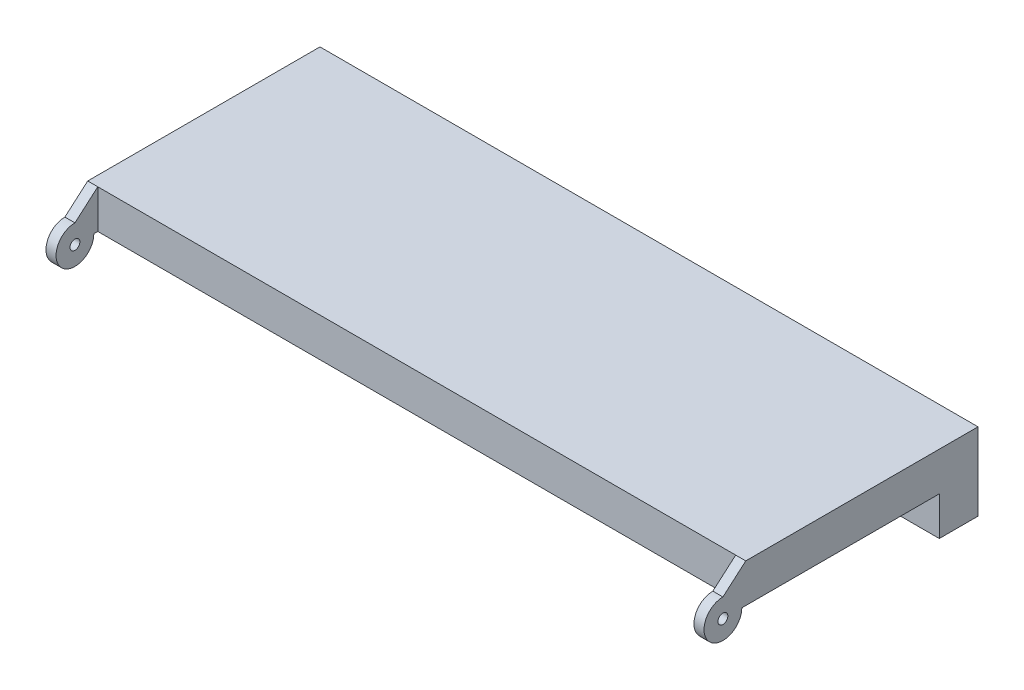
SolidWorks part; units mm, degrees
ref_plane "Front Plane" through (0, 0, 0) normal (0, 0, 1) x (1, 0, 0)
ref_plane "Top Plane" through (0, 0, 0) normal (0, 1, 0) x (1, 0, 0)
ref_plane "Right Plane" through (0, 0, 0) normal (1, 0, 0) x (0, 0, -1)
sketch "Sketch1" plane through (0, 0, 0) normal (0, 1, 0) x (1, 0, 0)
  line L1 (0, 0) -> (85, 0)
  line L2 (0, 0) -> (0, 30)
  line L3 (0, 30) -> (85, 30)
  line L4 (85, 0) -> (85, 30)
  dimension "D1" = 85
  dimension "D2" = 30
extrude "Top surface" add sketch "Sketch1" along normal blind 10
sketch "Sketch6" plane through (0, 0, 0) normal (-1, 0, 0) x (0, 0, 1)
  line L1 (0, 0) -> (-25, 0)
  line L2 (0, 0) -> (0, 5)
  line L3 (0, 5) -> (-25, 5)
  line L4 (-25, 0) -> (-25, 5)
  dimension "D1" = 5
  dimension "D2" = 25
extrude "Top surface cut" cut sketch "Sketch6" against normal through all
sketch "Sketch16" plane through (0, 0, 0) normal (-1, 0, 0) x (0, 0, 1)
  line L0 (0, 5) -> (2.95, 5) construction
  line L1 (2.95, 7.44) -> (0, 10)
  line L2 (0, 10) -> (0, 5) construction
  line L5 (0, 5) -> (0.51, 5)
  line L6 (0, 10) -> (0, 5)
  circle A0 centre (2.95, 5) radius 2.44
  circle A1 centre (2.95, 5) radius 0.64
  dimension "D2" = 4.88
  dimension "D3" = 1.28
  dimension "D1" = 2.95
  dimension "D4" = 1.8429
extrude "Boss-Extrude14" add sketch "Sketch16" against normal blind 1.3
pattern_linear "LPattern3" count 2 spacing 83.7 along (1, 0, 0) of "Boss-Extrude14"
